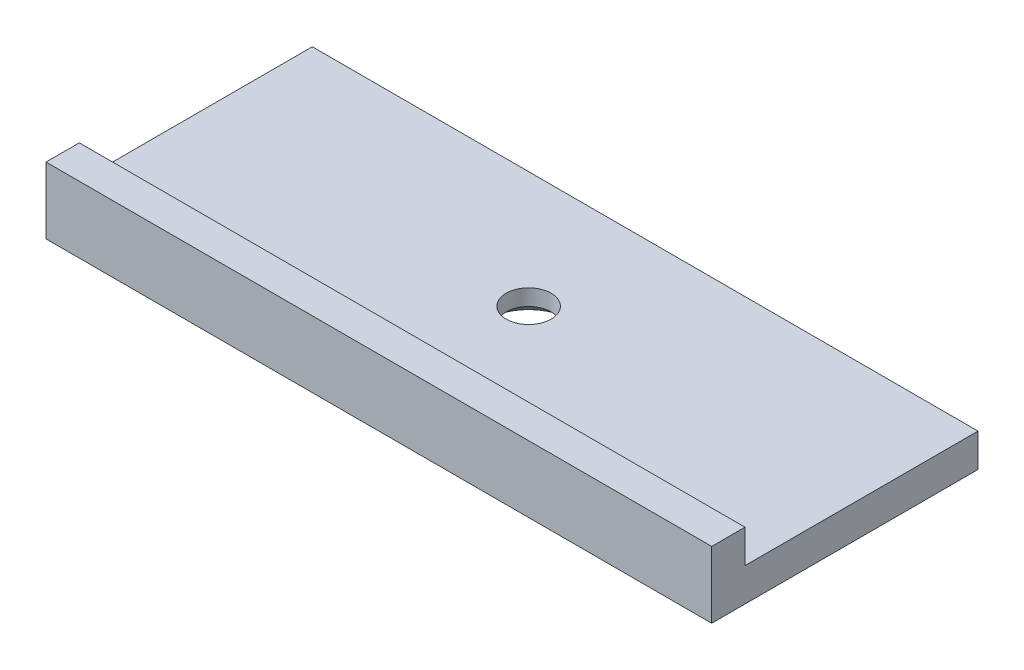
SolidWorks part; units mm, degrees
ref_plane "Front Plane" through (0, 0, 0) normal (0, 0, 1) x (1, 0, 0)
ref_plane "Top Plane" through (0, 0, 0) normal (0, 1, 0) x (1, 0, 0)
ref_plane "Right Plane" through (0, 0, 0) normal (1, 0, 0) x (0, 0, -1)
sketch "Sketch1" plane through (0, 0, 0) normal (0, 1, 0) x (1, 0, 0)
  line L1 (-50, -17.5) -> (50, -17.5)
  line L2 (-50, -17.5) -> (-50, 17.5)
  line L3 (-50, 17.5) -> (50, 17.5)
  line L4 (50, -17.5) -> (50, 17.5)
  line L5 (-50, -17.5) -> (50, 17.5) construction
  line L6 (-50, 17.5) -> (50, -17.5) construction
  point P0 (0, 0)
  dimension "D1" = 35
  dimension "D2" = 100
extrude "Boss-Extrude1" add sketch "Sketch1" along normal blind 5
sketch "Sketch2" plane through (0, 0, 0) normal (0, 1, 0) x (1, 0, 0)
  line L0 (-50, -17.5) -> (-50, -28.5135) construction
  line L2 (50, -17.5) -> (-50, -17.5)
  line L3 (50, -17.5) -> (50, -22.5)
  line L4 (50, -22.5) -> (-50, -22.5)
  line L5 (-50, -17.5) -> (-50, -22.5)
  dimension "D1" = 5
extrude "Boss-Extrude2" add sketch "Sketch2" along normal blind 10
hole_wizard "CSK for 1/4 Flat Head Machine Screw (100)1" positions "Sketch4" profile "Sketch5" countersink size "1/4" standard "ANSI Inch" end condition through all
sketch "Sketch4" plane through (0, 0, 0) normal (0, -1, 0) x (-1, 0, 0)
  point P0 (0, 0)
sketch "Sketch5" plane through (0, 0, 0) normal (1, 0, 0) x (0, 0, -1)
  line L0 (0, 0) -> (0, 10)
  line L1 (0, 10) -> (3.3782, 10)
  line L2 (3.3782, 10) -> (3.3782, 2.5682)
  line L3 (3.3782, 2.5682) -> (6.4389, 0)
  line L5 (6.4389, 0) -> (0, 0)
  line L6 (-3.3782, 2.5682) -> (-6.4389, 0) construction
  line L11 (0, -6.35) -> (0, 107.95) construction
  dimension "Thru Hole Dia." = 6.7564
  dimension "Thru Hole Depth" = 10
  dimension "Near C'Sink Dia." = 12.8778
  dimension "Near C'Sink Angle" = 100
